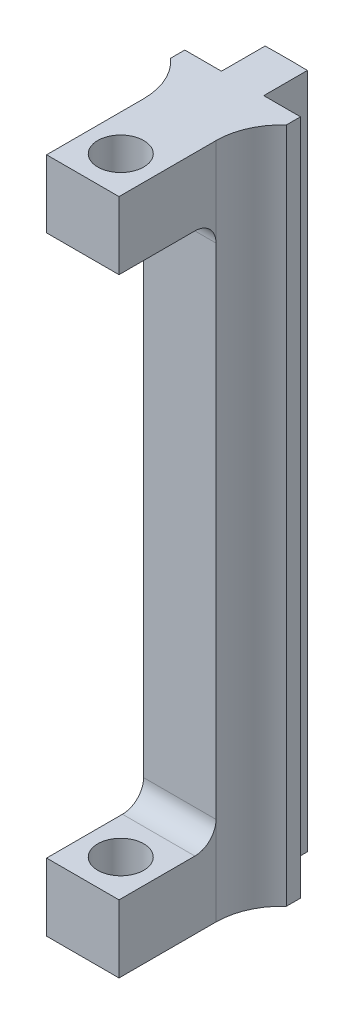
SolidWorks part; units mm, degrees
ref_plane "Front Plane" through (0, 0, 0) normal (0, 0, 1) x (1, 0, 0)
ref_plane "Top Plane" through (0, 0, 0) normal (0, 1, 0) x (1, 0, 0)
ref_plane "Right Plane" through (0, 0, 0) normal (1, 0, 0) x (0, 0, -1)
sketch "Sketch1" plane through (0, 0, 0) normal (0, 1, 0) x (1, 0, 0)
  line L0 (-2.7181, 75.8155) -> (2.7181, 75.8155)
  line L1 (8.1401, 80.7182) -> (8.1401, 83.4238)
  line L2 (-8.1401, 80.7182) -> (-8.1401, 83.4238)
  line L3 (0, 75.8155) -> (0, 87.8958) construction
  line L4 (2.7181, 75.8155) -> (2.7181, 62.9548) construction
  arc A0 (2.7181, 75.8155) -> (8.1401, 80.7182) centre (7.6457, 75.8155) cw
  arc A1 (8.1401, 83.4238) -> (-8.1401, 83.4238) centre (0, 0) ccw
  arc A2 (-2.7181, 75.8155) -> (-8.1401, 80.7182) centre (-7.6457, 75.8155) ccw
  arc A3 (8.1401, 80.7182) -> (20.3966, 78.5217) centre (0, 0) cw construction
  point P11 (2.7181, 71.1201)
  point P12 (2.7181, 76.0541)
  dimension "D2" = 81.1276
  dimension "D3" = 83.82
  dimension "D4" = 4.9276
  dimension "D1" = 2.7181
extrude "Boss-Extrude1" add sketch "Sketch1" against normal blind 50.8
sketch "Sketch3" plane through (0, 0, 0) normal (0, 1, 0) x (1, 0, 0)
  line L0 (-4.3408, 80.5281) -> (-1.5875, 80.5281)
  line L1 (-2.7181, 75.8155) -> (2.7181, 75.8155) construction
  line L2 (0, 83.82) -> (0, 75.8155) construction
  line L3 (-4.3408, 80.5281) -> (-4.3408, 76.768)
  line L4 (-4.3408, 76.768) -> (-9.7396, 76.768)
  line L5 (-9.7396, 76.768) -> (-9.7396, 86.1044)
  line L6 (-4.5117, 83.6985) -> (-4.3408, 80.5281) construction
  line L7 (-4.5117, 83.6985) -> (46.925, 86.4711) construction
  line L8 (0, 83.82) -> (-1.5875, 83.82)
  line L9 (-3.175, 86.1044) -> (-9.7396, 86.1044)
  line L10 (-1.5875, 83.82) -> (-1.5875, 80.5281)
  arc A0 (8.1401, 83.4238) -> (-8.1401, 83.4238) centre (0, 0) ccw construction
  arc A1 (-2.7181, 75.8155) -> (-8.1401, 80.7182) centre (-7.6457, 75.8155) ccw construction
  point P14 (-4.3408, 79.4704)
  point P18 (0, 0)
  dimension "D1" = 3.175
  dimension "D2" = 1.5875
extrude "Cut-Extrude1" cut sketch "Sketch3" against normal through all
mirror "Mirror2" about plane through (0, 0, 0) normal (1, 0, 0) of "Cut-Extrude1"
sketch "Sketch2" plane through (0, 0, 0) normal (0, 1, 0) x (1, 0, 0)
  line L1 (2.7181, 75.8155) -> (-2.7181, 75.8155)
  line L2 (2.7181, 75.8155) -> (2.7181, 68.5315)
  line L3 (2.7181, 68.5315) -> (-2.7181, 68.5315)
  line L4 (-2.7181, 75.8155) -> (-2.7181, 68.5315)
  point P5 (0, 0)
  point P6 (0, 0)
  dimension "D1" = 7.2839
extrude "Boss-Extrude2" add sketch "Sketch2" against normal blind 5.08
fillet "Fillet1" radius 1.5875 1 edges at (0, -5.08, -75.8155)
ref_plane "midplane" through (0, -25.4, 0) normal (0, -1, 0) x (-1, 0, 0)
mirror "Mirror1" about plane through (0, -25.4, 0) normal (0, -1, 0) of "Boss-Extrude2", "Fillet1"
hole_wizard "#4 Clearance Hole1" positions "Sketch4" profile "Sketch5" hole size "#4" standard "ANSI Inch" end condition through all
sketch "Sketch4" plane through (0, 0, 0) normal (0, 1, 0) x (1, 0, 0)
  line L0 (0, 68.5315) -> (0, 74.228) construction
  line L2 (-2.7181, 68.5315) -> (2.7181, 68.5315) construction
  line L3 (-2.7181, 74.228) -> (2.7181, 74.228) construction
  point P0 (0, 71.3797)
  point P6 (0, 0)
  point P10 (0, 0)
  point P13 (0, 0)
  point P14 (0, 0)
sketch "Sketch5" plane through (0, 0, -71.3797) normal (1, 0, 0) x (0, 0, 1)
  line L0 (0, 0) -> (0, 50.8)
  line L1 (0, 50.8) -> (1.7272, 50.8)
  line L2 (1.7272, 50.8) -> (1.7272, 0)
  line L5 (1.7272, 0) -> (0, 0)
  line L11 (0, -6.35) -> (0, 107.95) construction
  dimension "Thru Hole Dia." = 3.4544
  dimension "Thru Hole Depth" = 50.8
